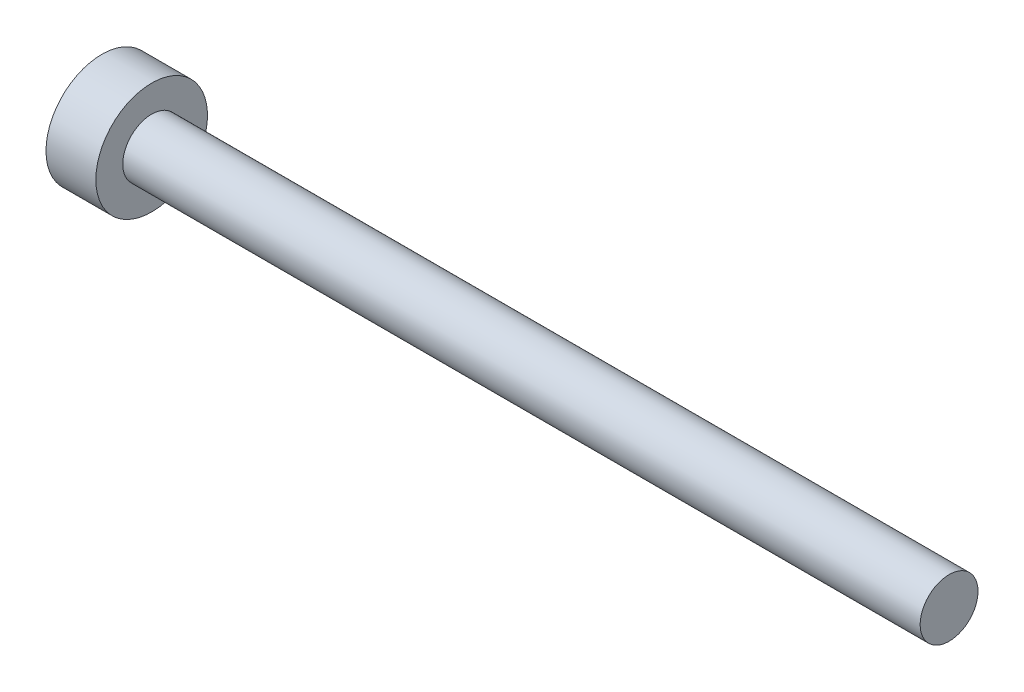
SolidWorks part; units mm, degrees
ref_plane "Ön Düzlem" through (0, 0, 0) normal (0, 0, 1) x (1, 0, 0)
ref_plane "Üst Düzlem" through (0, 0, 0) normal (0, 1, 0) x (1, 0, 0)
ref_plane "Sağ Düzlem" through (0, 0, 0) normal (1, 0, 0) x (0, 0, -1)
sketch "Çizim1" plane through (0, 0, 0) normal (1, 0, 0) x (0, 0, -1)
  circle A0 centre (0, 0) radius 1.45
  dimension "D1" = 2.9
extrude "Yükseklik-Ekstrüzyon1" add sketch "Çizim1" along normal blind 40
sketch "Çizim2" plane through (0, 0, 0) normal (-1, 0, 0) x (0, 0, 1)
  circle A0 centre (0, 0) radius 2.8
  dimension "D1" = 5.6
extrude "Yükseklik-Ekstrüzyon2" add sketch "Çizim2" along normal blind 2.5
sketch "Çizim3" plane through (-2.5, 0, 0) normal (-1, 0, 0) x (0, 0, 1)
  line L1 (0.866, -1.5) -> (1.7321, 0)
  line L2 (1.7321, 0) -> (0.866, 1.5)
  line L3 (0.866, 1.5) -> (-0.866, 1.5)
  line L4 (-0.866, 1.5) -> (-1.7321, 0)
  line L5 (-1.7321, 0) -> (-0.866, -1.5)
  line L6 (-0.866, -1.5) -> (0.866, -1.5)
  circle A0 centre (0, 0) radius 1.5 construction
  dimension "D1" = 3
extrude "Kes-Ekstrüzyon1" cut sketch "Çizim3" against normal blind 2
